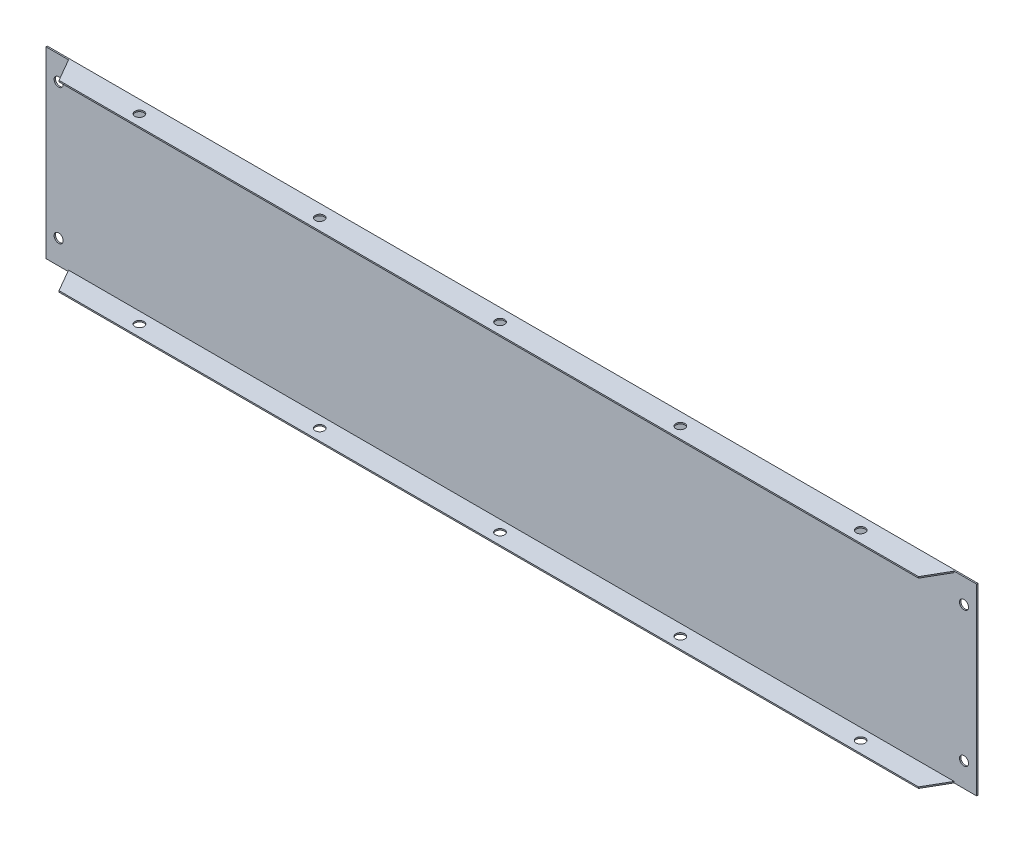
SolidWorks part; units mm, degrees
material "AISI 316 Нержавеющая сталь, лист (SS)"
ref_plane "Спереди" through (0, 0, 0) normal (0, 0, 1) x (1, 0, 0)
ref_plane "Сверху" through (0, 0, 0) normal (0, 1, 0) x (1, 0, 0)
ref_plane "Справа" through (0, 0, 0) normal (1, 0, 0) x (0, 0, -1)
other "Configuration Table"
sketch "Эскиз1" plane through (0, 0, 0) normal (0, 0, 1) x (1, 0, 0)
  line L0 (5.4, 75.5) -> (11.4, 75.5) construction
  line L1 (0, 81.4) -> (482.2, 81.4)
  line L2 (0, 81.4) -> (0, 0)
  line L3 (0, 0) -> (482.2, 0)
  line L4 (482.2, 81.4) -> (482.2, 0)
  line L5 (5.4, 79.5) -> (11.4, 79.5)
  line L6 (5.4, 71.5) -> (11.4, 71.5)
  line L7 (5.4, 5.9) -> (11.4, 5.9) construction
  line L8 (5.4, 9.9) -> (11.4, 9.9)
  line L9 (5.4, 1.9) -> (11.4, 1.9)
  line L10 (470.8, 5.9) -> (476.8, 5.9) construction
  line L11 (470.8, 9.9) -> (476.8, 9.9)
  line L12 (470.8, 1.9) -> (476.8, 1.9)
  line L13 (470.8, 75.5) -> (476.8, 75.5) construction
  line L14 (470.8, 79.5) -> (476.8, 79.5)
  line L15 (470.8, 71.5) -> (476.8, 71.5)
  line L16 (241.1, 81.4) -> (241.1, 0) construction
  line L17 (34.65, 81.4) -> (447.55, 81.4)
  line L18 (34.65, 81.4) -> (34.65, 0)
  line L19 (34.65, 0) -> (447.55, 0)
  line L20 (447.55, 81.4) -> (447.55, 0)
  line L21 (34.65, 40.7) -> (447.55, 40.7) construction
  arc A0 (5.4, 79.5) -> (5.4, 71.5) centre (5.4, 75.5) ccw
  arc A1 (11.4, 71.5) -> (11.4, 79.5) centre (11.4, 75.5) ccw
  arc A2 (5.4, 9.9) -> (5.4, 1.9) centre (5.4, 5.9) ccw
  arc A3 (11.4, 1.9) -> (11.4, 9.9) centre (11.4, 5.9) ccw
  arc A4 (470.8, 9.9) -> (470.8, 1.9) centre (470.8, 5.9) ccw
  arc A5 (476.8, 1.9) -> (476.8, 9.9) centre (476.8, 5.9) ccw
  arc A6 (470.8, 79.5) -> (470.8, 71.5) centre (470.8, 75.5) ccw
  arc A7 (476.8, 71.5) -> (476.8, 79.5) centre (476.8, 75.5) ccw
  circle A8 centre (40.25, 70.7) radius 2
  circle A9 centre (441.95, 70.7) radius 2
  circle A10 centre (441.95, 10.7) radius 2
  circle A11 centre (40.25, 10.7) radius 2
  circle A12 centre (40.25, 40.7) radius 2
  circle A13 centre (441.95, 40.7) radius 2
  point P7 (8.4, 75.5)
  point P15 (8.4, 5.9)
  point P23 (473.8, 5.9)
  point P30 (473.8, 75.5)
  dimension "D14" = 4
  dimension "D19" = 4
  dimension "D20" = 4
  dimension "D1" = 482.2
  dimension "D2" = 81.4
  dimension "D3" = 8
  dimension "D4" = 6
  dimension "D5" = 5.9
  dimension "D6" = 8.4
  dimension "D7" = 8.4
  dimension "D8" = 5.9
  dimension "D9" = 8.4
  dimension "D10" = 5.9
  dimension "D11" = 8.4
  dimension "D12" = 5.9
  dimension "D13" = 412.9
  dimension "D17" = 401.7
  dimension "D18" = 60
  dimension "D15" = 2
  dimension "D16" = 2
extrude "Бобышка-Вытянуть1" add sketch "Эскиз1" along normal blind 0.6 contours L20 L1 L18 L3 A11 A10 A9 A8 | A12 | A13
sketch "Эскиз2" plane through (0, 81.4, 0) normal (0, 1, 0) x (1, 0, 0)
  line L0 (44.65, -0.6) -> (50.4235, -10.6)
  line L1 (34.65, -0.6) -> (447.55, -0.6) construction
  line L2 (50.4235, -10.6) -> (431.7765, -10.6)
  line L3 (431.7765, -10.6) -> (437.55, -0.6)
  line L4 (437.55, -0.6) -> (44.65, -0.6)
  line L5 (241.1, -10.6) -> (241.1, -0.6) construction
  line L6 (401.1, -5.6) -> (321.1, -5.6) construction
  circle A0 centre (401.1, -5.6) radius 2
  circle A1 centre (321.1, -5.6) radius 2
  circle A2 centre (241.1, -5.6) radius 2
  circle A3 centre (161.1, -5.6) radius 2
  circle A4 centre (81.1, -5.6) radius 2
  dimension "D6" = 4
  dimension "D1" = 60
  dimension "D2" = 60
  dimension "D3" = 10
  dimension "D4" = 10
  dimension "D5" = 10
  dimension "D7" = 80
extrude "Бобышка-Вытянуть2" add sketch "Эскиз2" against normal blind 0.6
sketch "Эскиз3" plane through (0, 0, 0) normal (0, -1, 0) x (1, 0, 0)
  line L4 (44.65, 0.6) -> (437.55, 0.6)
  line L5 (437.55, 0.6) -> (431.7765, 10.6)
  line L6 (431.7765, 10.6) -> (50.4235, 10.6)
  line L7 (50.4235, 10.6) -> (44.65, 0.6)
  line L8 (44.65, 0.6) -> (437.55, 0.6)
  line L9 (437.55, 0.6) -> (431.7765, 10.6)
  line L10 (431.7765, 10.6) -> (50.4235, 10.6)
  line L11 (50.4235, 10.6) -> (44.65, 0.6)
  circle A0 centre (401.1, 5.6) radius 2 construction
  circle A1 centre (321.1, 5.6) radius 2 construction
  circle A2 centre (241.1, 5.6) radius 2 construction
  circle A3 centre (161.1, 5.6) radius 2 construction
  circle A4 centre (81.1, 5.6) radius 2 construction
  circle A5 centre (401.1, 5.6) radius 2
  circle A6 centre (321.1, 5.6) radius 2
  circle A7 centre (241.1, 5.6) radius 2
  circle A8 centre (161.1, 5.6) radius 2
  circle A9 centre (81.1, 5.6) radius 2
  dimension "D1" = 0
extrude "Бобышка-Вытянуть3" add sketch "Эскиз3" against normal blind 0.6
